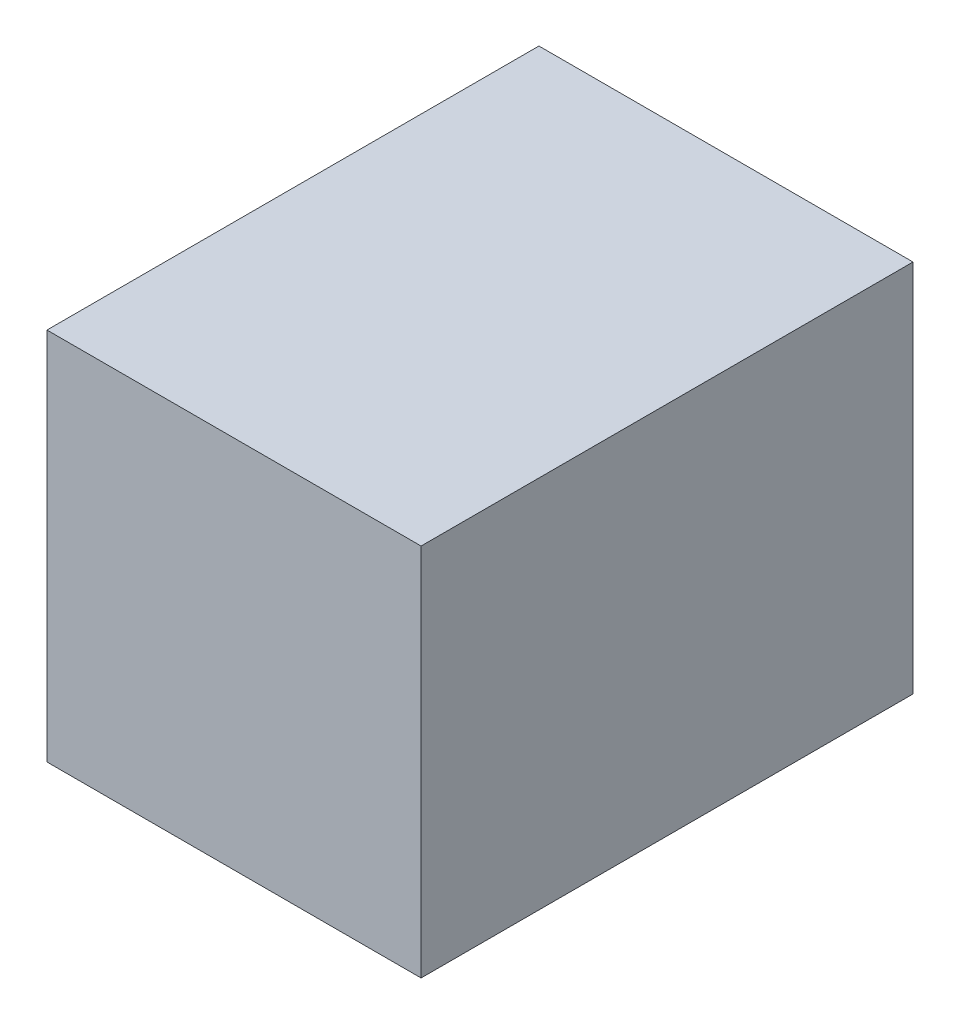
SolidWorks part; units mm, degrees
ref_plane "Front Plane" through (0, 0, 0) normal (0, 0, 1) x (1, 0, 0)
ref_plane "Top Plane" through (0, 0, 0) normal (0, 1, 0) x (1, 0, 0)
ref_plane "Right Plane" through (0, 0, 0) normal (1, 0, 0) x (0, 0, -1)
sketch "Sketch1" plane through (0, 0, 0) normal (0, 1, 0) x (1, 0, 0)
  line L1 (-5, 6.575) -> (5, 6.575)
  line L2 (-5, 6.575) -> (-5, -6.575)
  line L3 (-5, -6.575) -> (5, -6.575)
  line L4 (5, 6.575) -> (5, -6.575)
  line L5 (-5, 6.575) -> (5, -6.575) construction
  line L6 (-5, -6.575) -> (5, 6.575) construction
  point P0 (0, 0)
  dimension "D1" = 13.15
  dimension "D2" = 10
extrude "Boss-Extrude1" add sketch "Sketch1" along normal blind 10
